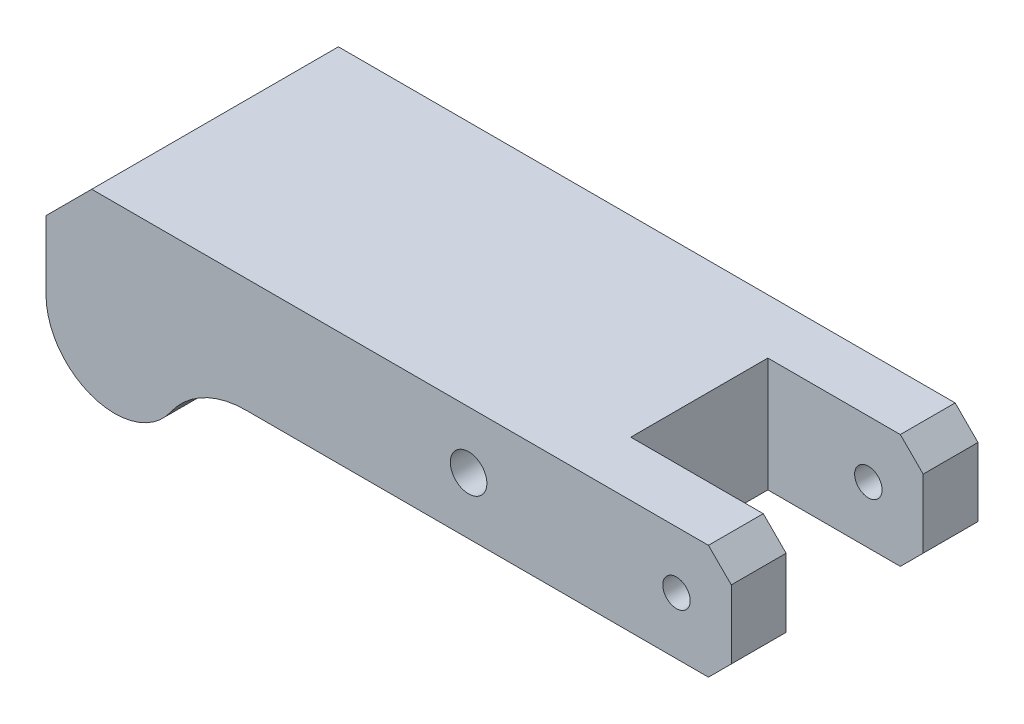
SolidWorks part; units mm, degrees
ref_plane "Front Plane" through (0, 0, 0) normal (0, 0, 1) x (1, 0, 0)
ref_plane "Top Plane" through (0, 0, 0) normal (0, 1, 0) x (1, 0, 0)
ref_plane "Right Plane" through (0, 0, 0) normal (1, 0, 0) x (0, 0, -1)
sketch "Sketch1" plane through (0, 0, 0) normal (0, 0, 1) x (1, 0, 0)
  line L1 (0, 0) -> (-106.2772, 0)
  line L2 (0, 0) -> (0, 25)
  line L3 (0, 25) -> (-150, 25)
  line L4 (-150, 0) -> (-150, 25)
  arc A0 (-150, 0) -> (-122.6902, -8.5714) centre (-135, 0) ccw
  arc A1 (-122.6902, -8.5714) -> (-106.2772, 0) centre (-106.2772, -20) cw
  circle A2 centre (-12, 12.5) radius 3
  circle A3 centre (-57.5, 12.5) radius 4
  point P13 (0, 0)
  dimension "D3" = 30
  dimension "D4" = 20
  dimension "D5" = 6
  dimension "D6" = 8
  dimension "D1" = 150
  dimension "D2" = 25
  dimension "D7" = 12
  dimension "D8" = 45.5
  dimension "D9" = 12.5
extrude "Boss-Extrude1" add sketch "Sketch1" along normal mid plane 54
chamfer "Chamfer1" distance 10 angle 45 1 edges at (-150, 25, 0)
chamfer "Chamfer2" distance 5 angle 45 2 edges at (0, 0, 0) (0, 25, 0)
sketch "Sketch2" plane through (0, 25, 0) normal (0, 1, 0) x (1, 0, 0)
  line L0 (0, 27) -> (0, -27) construction
  line L1 (14.3135, 15) -> (-34, 15)
  line L2 (14.3135, 15) -> (14.3135, -15)
  line L3 (14.3135, -15) -> (-34, -15)
  line L4 (-34, 15) -> (-34, -15)
  dimension "D1" = 12
  dimension "D2" = 12
  dimension "D3" = 34
extrude "Cut-Extrude1" cut sketch "Sketch2" against normal through all
